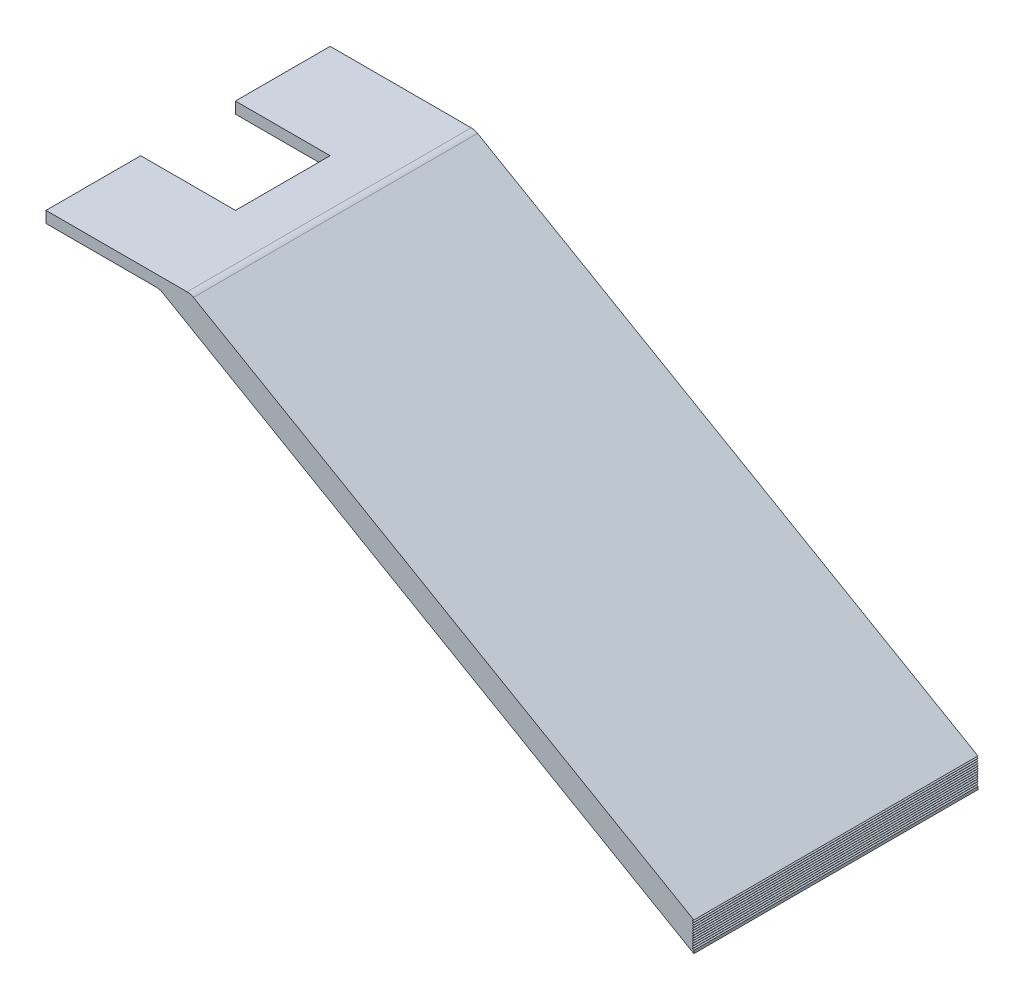
SolidWorks part; units mm, degrees
ref_plane "前视基准面" through (0, 0, 0) normal (0, 0, 1) x (1, 0, 0)
ref_plane "上视基准面" through (0, 0, 0) normal (0, 1, 0) x (1, 0, 0)
ref_plane "右视基准面" through (0, 0, 0) normal (1, 0, 0) x (0, 0, -1)
sketch "草图1" plane through (0, 0, 0) normal (1, 0, 0) x (0, 0, -1)
  line L1 (-22.5, 0.9) -> (22.5, 0.9)
  line L2 (-22.5, 0.9) -> (-22.5, -0.9)
  line L3 (-22.5, -0.9) -> (22.5, -0.9)
  line L4 (22.5, 0.9) -> (22.5, -0.9)
  line L5 (-22.5, 0.9) -> (22.5, -0.9) construction
  line L6 (-22.5, -0.9) -> (22.5, 0.9) construction
  point P0 (0, 0)
  dimension "D1" = 1.8
  dimension "D2" = 45
extrude "凸台-拉伸1" add sketch "草图1" along normal blind 18
sketch "草图2" plane through (0, 0.9, 0) normal (0, 1, 0) x (1, 0, 0)
  line L0 (0, 7.5) -> (15, 7.5)
  line L1 (0, 22.5) -> (0, -22.5) construction
  line L2 (15, 7.5) -> (15, -7.5)
  line L3 (15, -7.5) -> (0, -7.5)
  line L4 (0, -7.5) -> (0, 7.5)
  point P6 (15, 0)
  dimension "D1" = 15
  dimension "D2" = 15
extrude "切除-拉伸1" cut sketch "草图2" against normal blind 15
sketch "草图4" plane through (0, 0, -22.5) normal (0, 0, -1) x (-1, 0, 0)
  line L0 (-18, -0.9) -> (-102.6025, -49.7453)
  line L1 (-102.6025, -49.7453) -> (-104.6025, -46.2812)
  line L2 (-104.6025, -46.2812) -> (-22.8823, 0.9)
  line L3 (-18, 0.9) -> (-18, -0.9)
  line L4 (-18, -0.9) -> (0, -0.9) construction
  line L5 (-18, 0.9) -> (-22.8823, 0.9)
  line L6 (-18, 0.9) -> (0, 0.9) construction
  dimension "D1" = 150
  dimension "D3" = 4
extrude "凸台-拉伸2" add sketch "草图4" against normal up to surface (45 mm away) up to face at (9, 0, 22.5)
sketch "草图5" plane through (0, 0, 22.5) normal (0, 0, 1) x (1, 0, 0)
  line L0 (102.6025, -45.1265) -> (102.6025, -49.7453)
  line L1 (104.6025, -46.2812) -> (22.8823, 0.9) construction
  line L2 (102.6025, -49.7453) -> (104.6025, -46.2812)
  line L3 (104.6025, -46.2812) -> (102.6025, -45.1265)
extrude "切除-拉伸2" cut sketch "草图5" against normal up to surface (45 mm away) up to face at (41.3479, -16.0044, -22.5)
sketch "草图6" plane through (0, 0, 22.5) normal (0, 0, 1) x (1, 0, 0)
  line L0 (102.6025, -45.1265) -> (102.3495, -45.2877)
  line L1 (102.3495, -45.2877) -> (102.6025, -45.4488)
  line L2 (102.6025, -45.1265) -> (102.6025, -49.7453) construction
  line L3 (102.3495, -45.2877) -> (103.4369, -45.2877) construction
  line L4 (102.6025, -45.1265) -> (102.6025, -45.4488)
  line L23 (102.6025, -45.4765) -> (102.3495, -45.6377)
  line L24 (102.3495, -45.6377) -> (102.6025, -45.7988)
  line L25 (102.6025, -45.4765) -> (102.6025, -45.7988)
  line L26 (102.6025, -45.8265) -> (102.3495, -45.9877)
  line L27 (102.3495, -45.9877) -> (102.6025, -46.1488)
  line L28 (102.6025, -45.8265) -> (102.6025, -46.1488)
  line L29 (102.6025, -46.1765) -> (102.3495, -46.3377)
  line L30 (102.3495, -46.3377) -> (102.6025, -46.4988)
  line L31 (102.6025, -46.1765) -> (102.6025, -46.4988)
  line L32 (102.6025, -46.5265) -> (102.3495, -46.6877)
  line L33 (102.3495, -46.6877) -> (102.6025, -46.8488)
  line L34 (102.6025, -46.5265) -> (102.6025, -46.8488)
  line L35 (102.6025, -46.8765) -> (102.3495, -47.0377)
  line L36 (102.3495, -47.0377) -> (102.6025, -47.1988)
  line L37 (102.6025, -46.8765) -> (102.6025, -47.1988)
  line L38 (102.6025, -47.2265) -> (102.3495, -47.3877)
  line L39 (102.3495, -47.3877) -> (102.6025, -47.5488)
  line L40 (102.6025, -47.2265) -> (102.6025, -47.5488)
  line L41 (102.6025, -47.5765) -> (102.3495, -47.7377)
  line L42 (102.3495, -47.7377) -> (102.6025, -47.8988)
  line L43 (102.6025, -47.5765) -> (102.6025, -47.8988)
  line L44 (102.6025, -47.9265) -> (102.3495, -48.0877)
  line L45 (102.3495, -48.0877) -> (102.6025, -48.2488)
  line L46 (102.6025, -47.9265) -> (102.6025, -48.2488)
  line L47 (102.6025, -48.2765) -> (102.3495, -48.4377)
  line L48 (102.3495, -48.4377) -> (102.6025, -48.5988)
  line L49 (102.6025, -48.2765) -> (102.6025, -48.5988)
  line L50 (102.6025, -48.6265) -> (102.3495, -48.7877)
  line L51 (102.3495, -48.7877) -> (102.6025, -48.9488)
  line L52 (102.6025, -48.6265) -> (102.6025, -48.9488)
  line L53 (102.6025, -48.9765) -> (102.3495, -49.1377)
  line L54 (102.3495, -49.1377) -> (102.6025, -49.2988)
  line L55 (102.6025, -48.9765) -> (102.6025, -49.2988)
  dimension "D1" = 0.3
  dimension "D2" = 12
extrude "切除-拉伸3" cut sketch "草图6" against normal up to surface (45 mm away) up to face at (41.0146, -15.812, -22.5)
fillet "圆角1" radius 2 1 edges at (22.8823, 0.9, 0)
fillet "圆角2" radius 2 1 edges at (18, -0.9, 0)
